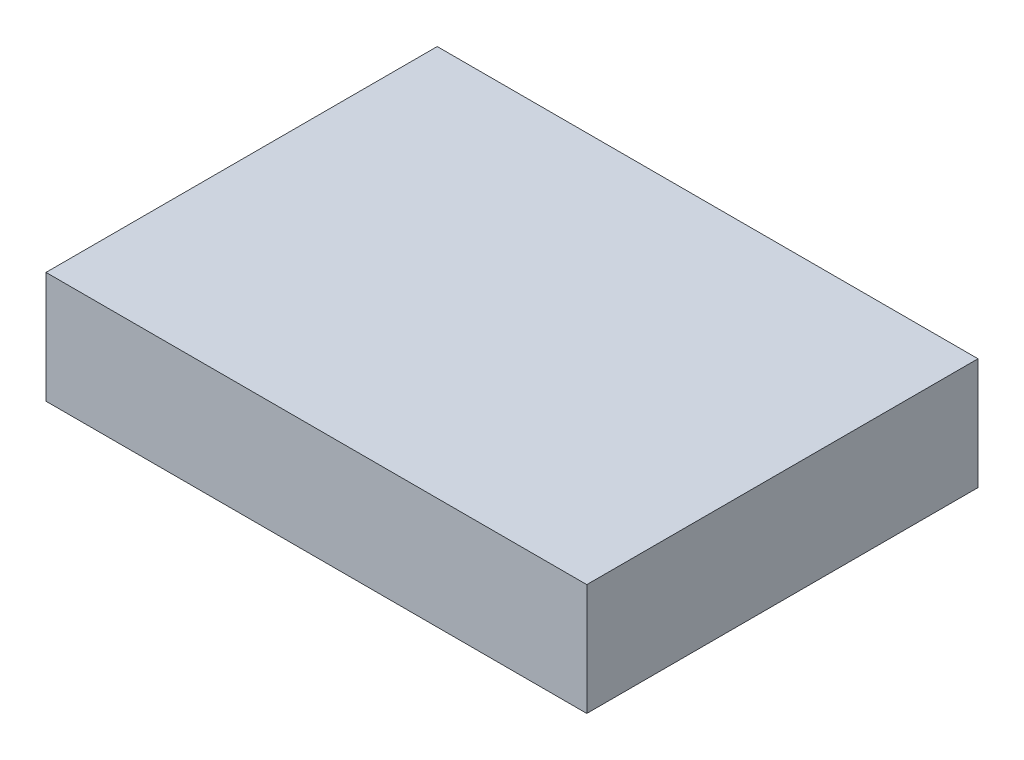
SolidWorks part; units mm, degrees
ref_plane "Plano frontal" through (0, 0, 0) normal (0, 0, 1) x (1, 0, 0)
ref_plane "Plano superior" through (0, 0, 0) normal (0, 1, 0) x (1, 0, 0)
ref_plane "Plano direito" through (0, 0, 0) normal (1, 0, 0) x (0, 0, -1)
sketch "Esboço1" plane through (0, 0, 0) normal (0, 1, 0) x (1, 0, 0)
  line L1 (-31.1883, 19.5893) -> (17.2695, 19.5893)
  line L2 (-31.1883, 19.5893) -> (-31.1883, -15.4653)
  line L3 (-31.1883, -15.4653) -> (17.2695, -15.4653)
  line L4 (17.2695, 19.5893) -> (17.2695, -15.4653)
extrude "Ressalto-extrusão1" add sketch "Esboço1" along normal blind 10
